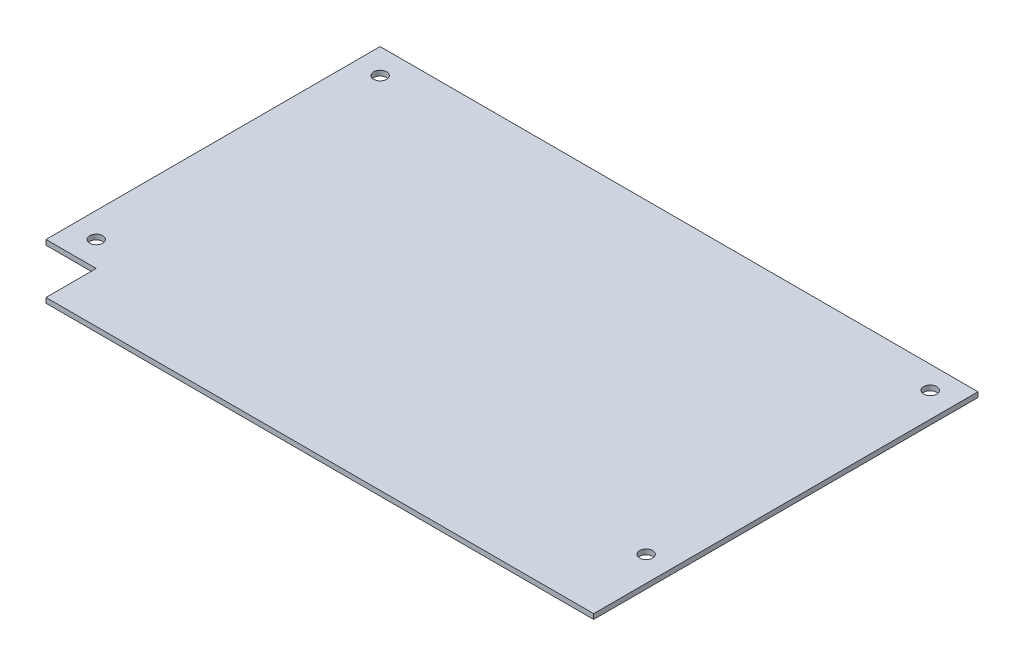
SolidWorks part; units mm, degrees
material "3.1645 (EN AW-2007)"
ref_plane "Přední rovina" through (0, 0, 0) normal (0, 0, 1) x (1, 0, 0)
ref_plane "Horní rovina" through (0, 0, 0) normal (0, 1, 0) x (1, 0, 0)
ref_plane "Pravá rovina" through (0, 0, 0) normal (1, 0, 0) x (0, 0, -1)
sketch "Skica1" plane through (0, 0, 0) normal (0, 1, 0) x (1, 0, 0)
  line L1 (119, -76.5) -> (-99, -76.5)
  line L2 (119, -76.5) -> (119, 76.5)
  line L3 (119, 76.5) -> (-119, 76.5)
  line L4 (-119, -56.5) -> (-119, 76.5)
  line L5 (119, -76.5) -> (-119, 76.5) construction
  line L6 (119, 76.5) -> (-99, -63.6429) construction
  line L9 (-119, -56.5) -> (-99, -56.5)
  line L10 (-99, -76.5) -> (-99, -56.5)
  point P0 (0, 0)
  dimension "D1" = 238
  dimension "D2" = 153
  dimension "D3" = 20
extrude "Přidat vysunutím1" add sketch "Skica1" along normal blind 2
sketch "Skica2" plane through (0, 0, 0) normal (0, -1, 0) x (1, 0, 0)
  line L0 (109, 48.7) -> (109, 45.6045) construction
  circle A0 centre (109, 45.6045) radius 2.6
  circle A1 centre (109, -67.4575) radius 2.6
  dimension "D1" = 5.2
extrude "Odebrat vysunutím1" cut sketch "Skica2" against normal blind 2
sketch "Skica3" plane through (0, 2, 0) normal (0, 1, 0) x (1, 0, 0)
  line L0 (-119, 76.5) -> (-119, -56.5) construction
  line L1 (119, 76.5) -> (-119, 76.5) construction
  line L2 (-119, -56.5) -> (-99, -56.5) construction
  circle A0 centre (-109, 66.5) radius 2.6
  circle A1 centre (-109, -46.5) radius 2.6
  dimension "D5" = 5.2
  dimension "D1" = 10
  dimension "D2" = 10
  dimension "D3" = 10
  dimension "D4" = 10
extrude "Odebrat vysunutím2" cut sketch "Skica3" against normal blind 2
